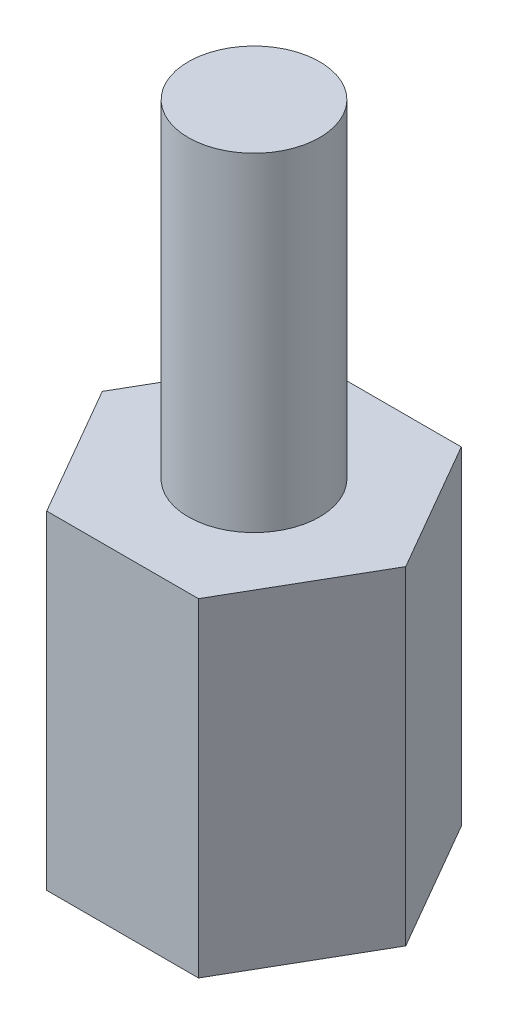
SolidWorks part; units mm, degrees
ref_plane "Front Plane" through (0, 0, 0) normal (0, 0, 1) x (1, 0, 0)
ref_plane "Top Plane" through (0, 0, 0) normal (0, 1, 0) x (1, 0, 0)
ref_plane "Right Plane" through (0, 0, 0) normal (1, 0, 0) x (0, 0, -1)
sketch "Sketch1" plane through (0, 0, 0) normal (0, 1, 0) x (1, 0, 0)
  circle A0 centre (0, 0) radius 1
  dimension "D1" = 2
extrude "Boss-Extrude1" add sketch "Sketch1" along normal blind 5
sketch "Sketch2" plane through (0, 0, 0) normal (0, 1, 0) x (1, 0, 0)
  line L1 (2.3094, 0) -> (1.1547, 2)
  line L2 (1.1547, 2) -> (-1.1547, 2)
  line L3 (-1.1547, 2) -> (-2.3094, 0)
  line L4 (-2.3094, 0) -> (-1.1547, -2)
  line L5 (-1.1547, -2) -> (1.1547, -2)
  line L6 (1.1547, -2) -> (2.3094, 0)
  circle A0 centre (0, 0) radius 2 construction
  dimension "D1" = 4
extrude "Boss-Extrude2" add sketch "Sketch2" against normal blind 5
sketch "Sketch3" plane through (0, -5, 0) normal (0, -1, 0) x (1, 0, 0)
  circle A0 centre (0, 0) radius 1
  dimension "D1" = 2
extrude "Cut-Extrude1" cut sketch "Sketch3" against normal blind 3
